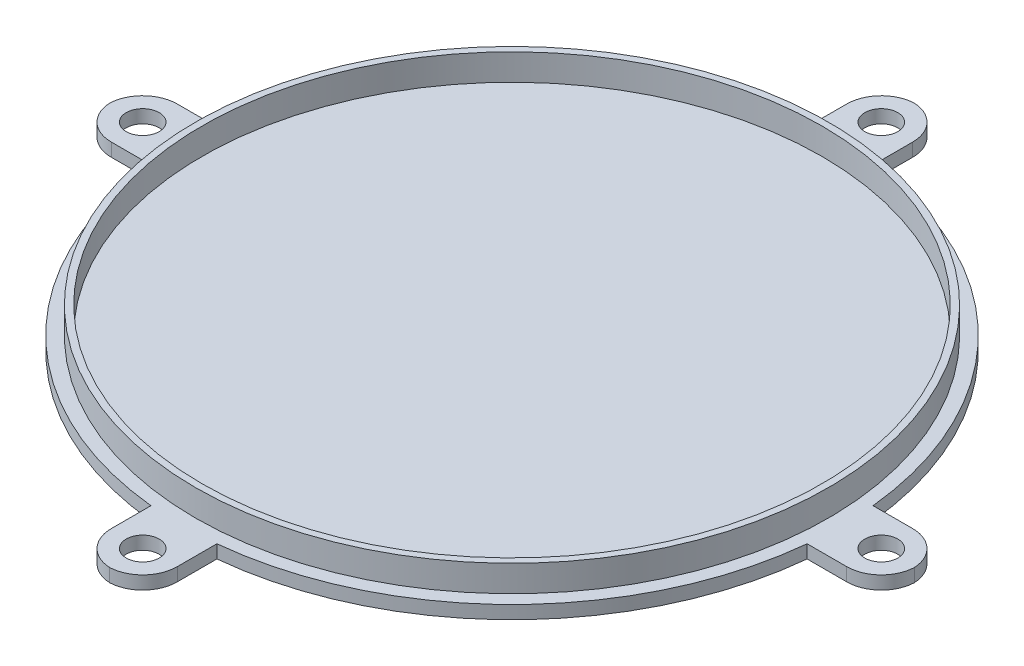
SolidWorks part; units mm, degrees
ref_plane "Front Plane" through (0, 0, 0) normal (0, 0, 1) x (1, 0, 0)
ref_plane "Top Plane" through (0, 0, 0) normal (0, 1, 0) x (1, 0, 0)
ref_plane "Right Plane" through (0, 0, 0) normal (1, 0, 0) x (0, 0, -1)
sketch "Sketch1" plane through (0, 0, 0) normal (0, 1, 0) x (1, 0, 0)
  circle A0 centre (0, 0) radius 50
  dimension "D1" = 100
extrude "Boss-Extrude1" add sketch "Sketch1" along normal blind 2
sketch "Sketch2" plane through (0, 2, 0) normal (0, 1, 0) x (1, 0, 0)
  circle A0 centre (0, 0) radius 48
  circle A1 centre (0, 0) radius 47
  dimension "D1" = 96
  dimension "D2" = 94
extrude "Boss-Extrude2" add sketch "Sketch2" along normal blind 4
sketch "Sketch3" plane through (0, 2, 0) normal (0, 1, 0) x (1, 0, 0)
  line L0 (0, 0) -> (-50, 0) construction
  line L1 (-50, 0) -> (-61, 0) construction
  line L2 (-55.7594, 5) -> (-49.7494, 5)
  line L3 (-55.7594, -5) -> (-49.7494, -5)
  line L4 (5, 55.7594) -> (5, 49.7494)
  line L5 (-5, 55.7594) -> (-5, 49.7494)
  line L6 (55.7594, -5) -> (49.7494, -5)
  line L7 (55.7594, 5) -> (49.7494, 5)
  line L8 (-5, -55.7594) -> (-5, -49.7494)
  line L9 (5, -55.7594) -> (5, -49.7494)
  circle A0 centre (0, 0) radius 50 construction
  arc A1 (-49.7494, 5) -> (-49.7494, -5) centre (0, 0) ccw
  arc A2 (-55.7594, 5) -> (-61, 0) centre (-55.7594, -0.2464) ccw
  arc A3 (-55.7594, -5) -> (-61, 0) centre (-55.7594, 0.2464) cw
  circle A4 centre (-56, 0) radius 2.5
  arc A5 (5, 55.7594) -> (0, 61) centre (-0.2464, 55.7594) ccw
  arc A6 (-5, 55.7594) -> (0, 61) centre (0.2464, 55.7594) cw
  circle A7 centre (0, 56) radius 2.5
  arc A8 (5, 49.7494) -> (-5, 49.7494) centre (0, 0) ccw
  arc A9 (55.7594, -5) -> (61, 0) centre (55.7594, 0.2464) ccw
  arc A10 (55.7594, 5) -> (61, 0) centre (55.7594, -0.2464) cw
  circle A11 centre (56, 0) radius 2.5
  arc A12 (49.7494, -5) -> (49.7494, 5) centre (0, 0) ccw
  arc A13 (-5, -55.7594) -> (0, -61) centre (0.2464, -55.7594) ccw
  arc A14 (5, -55.7594) -> (0, -61) centre (-0.2464, -55.7594) cw
  circle A15 centre (0, -56) radius 2.5
  arc A16 (-5, -49.7494) -> (5, -49.7494) centre (0, 0) ccw
  point P45 (0, 0)
  dimension "D4" = 5
  dimension "D1" = 11
  dimension "D2" = 6.01
  dimension "D3" = 5
  dimension "D5" = 5
  dimension "D6" = 4
extrude "Boss-Extrude3" add sketch "Sketch3" against normal blind 2
